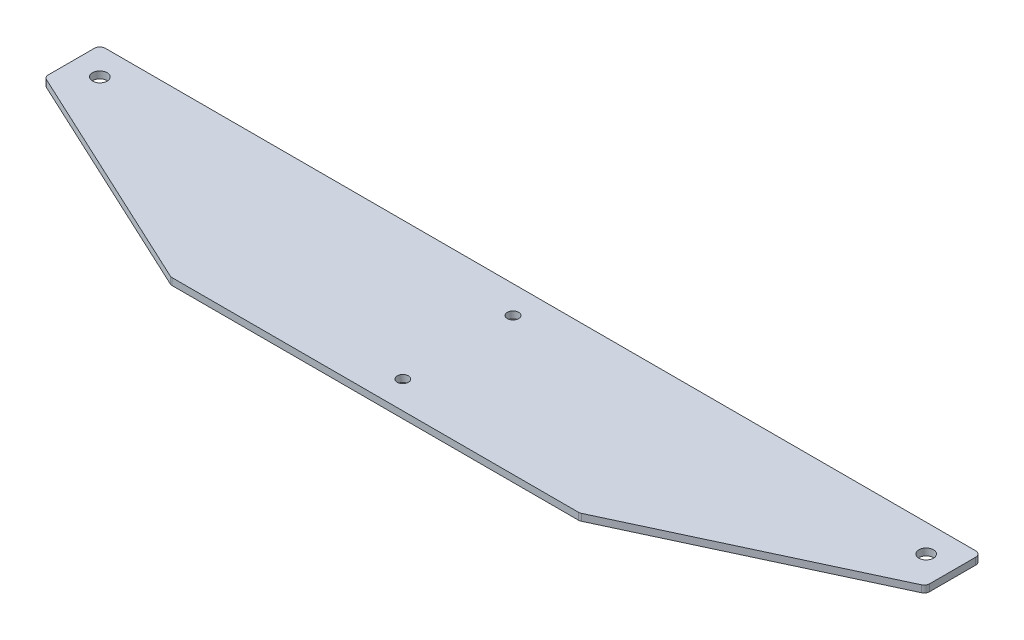
SolidWorks part; units mm, degrees
material "5052-O"
ref_plane "Front Plane" through (0, 0, 0) normal (0, 0, 1) x (1, 0, 0)
ref_plane "Top Plane" through (0, 0, 0) normal (0, 1, 0) x (1, 0, 0)
ref_plane "Right Plane" through (0, 0, 0) normal (1, 0, 0) x (0, 0, -1)
sketch "Sketch1" plane through (0, 0, 0) normal (0, 1, 0) x (1, 0, 0)
  line L1 (-203.2, -38.1) -> (203.2, -38.1)
  line L2 (-203.2, -38.1) -> (-203.2, 38.1)
  line L3 (-203.2, 38.1) -> (203.2, 38.1)
  line L4 (203.2, -38.1) -> (203.2, 38.1)
  line L5 (-203.2, -38.1) -> (203.2, 38.1) construction
  line L6 (-203.2, 38.1) -> (203.2, -38.1) construction
  circle A0 centre (-190.5, 25.4) radius 3.3734
  circle A1 centre (190.5, 25.4) radius 3.3734
  circle A2 centre (0, 25.4) radius 2.5797
  circle A3 centre (0, -25.4) radius 2.5797
  point P0 (0, 0)
  point P14 (0, -38.1)
  dimension "D3" = 5.1594
  dimension "D4" = 6.7469
  dimension "D5" = 12.7
  dimension "D6" = 12.7
  dimension "D7" = 12.7
  dimension "D8" = 12.7
  dimension "D9" = 12.7
  dimension "D10" = 12.7
  dimension "D1" = 406.4
  dimension "D2" = 76.2
extrude "Boss-Extrude1" add sketch "Sketch1" along normal blind 3.175
chamfer "Chamfer1" distance 50.8 angle 65 1 edges at (-203.2, 1.5875, 38.1)
chamfer "Chamfer2" distance 50.8 angle 65 1 edges at (203.2, 1.5875, 38.1)
fillet "Fillet1" radius 2.54 6 edges at (94.259, 1.5875, 38.1) (-94.259, 1.5875, 38.1) (-203.2, 1.5875, -12.7) (203.2, 1.5875, -12.7) (203.2, 1.5875, -38.1) (-203.2, 1.5875, -38.1)
